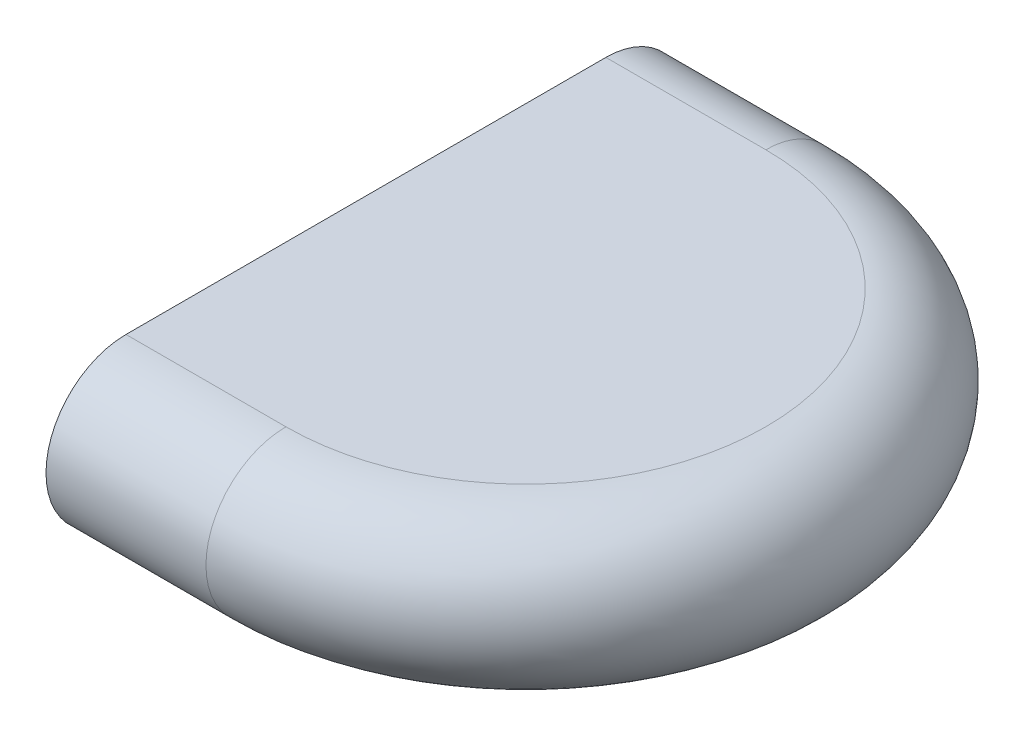
SolidWorks part; units mm, degrees
ref_plane "Piano frontale" through (0, 0, 0) normal (0, 0, 1) x (1, 0, 0)
ref_plane "Piano superiore" through (0, 0, 0) normal (0, 1, 0) x (1, 0, 0)
ref_plane "Piano destro" through (0, 0, 0) normal (1, 0, 0) x (0, 0, -1)
sketch "Schizzo2" plane through (0, 0, 0) normal (1, 0, 0) x (0, 0, -1)
  line L0 (3, 3.5418) -> (3, -1.4009) construction
  line L1 (3, 0) -> (6, 0)
  line L3 (3, 2) -> (6, 2)
  line L4 (3, 2) -> (3, 0)
  arc A0 (6, 0) -> (6, 2) centre (6, 1) ccw
  dimension "D1" = 2
  dimension "D2" = 2
  dimension "D3" = 3
  dimension "D4" = 3
revolve "Rivoluzione1" add sketch "Schizzo2" angle 180 about L0
sketch "Schizzo4" plane through (0, 0, 0) normal (-1, 0, 0) x (0, 0, 1)
  line L0 (0, 2) -> (-6, 2) construction
  line L1 (0, 2) -> (-6, 2)
  line L2 (-6, 0) -> (0, 0) construction
  line L3 (-6, 0) -> (0, 0)
  arc A0 (-6, 2) -> (-6, 0) centre (-6, 1) ccw construction
  arc A1 (0, 0) -> (0, 2) centre (0, 1) ccw construction
  arc A2 (-6, 2) -> (-6, 0) centre (-6, 1) ccw
  arc A3 (0, 0) -> (0, 2) centre (0, 1) ccw
extrude "Estrusione-Estrusione1" add sketch "Schizzo4" along normal blind 2
